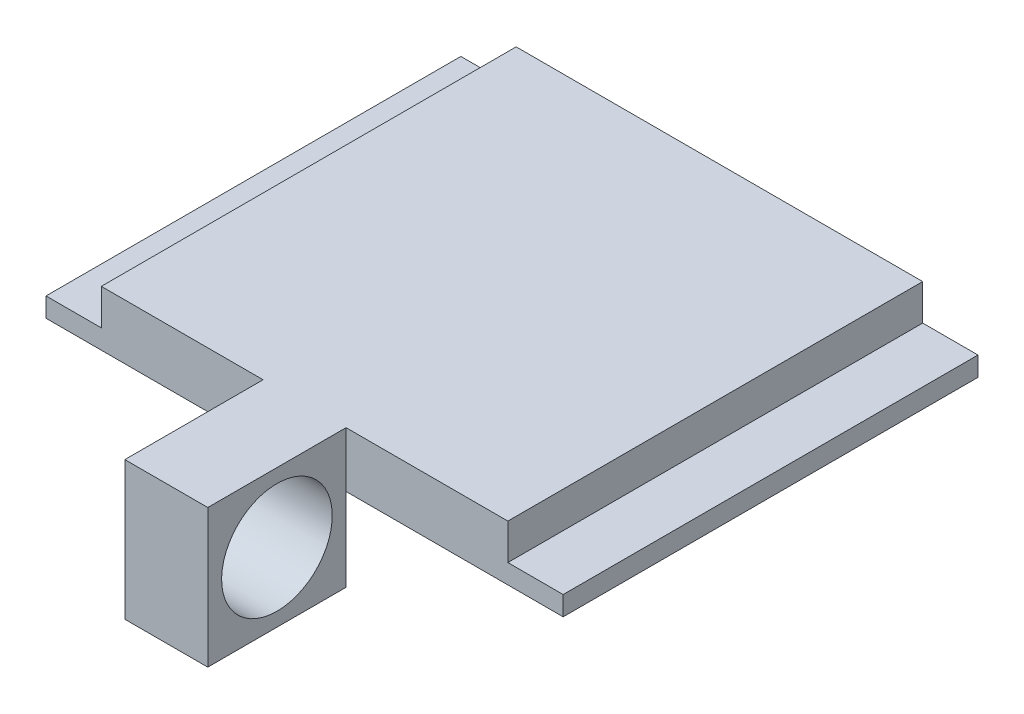
SolidWorks part; units mm, degrees
ref_plane "Front Plane" through (0, 0, 0) normal (0, 0, 1) x (1, 0, 0)
ref_plane "Top Plane" through (0, 0, 0) normal (0, 1, 0) x (1, 0, 0)
ref_plane "Right Plane" through (0, 0, 0) normal (1, 0, 0) x (0, 0, -1)
sketch "Sketch1" plane through (0, 0, 0) normal (0, 0, 1) x (1, 0, 0)
  line L16 (7.5, -0.65) -> (9.35, -0.65)
  line L17 (9.35, -0.65) -> (9.35, -1.35)
  line L18 (9.35, -1.35) -> (-9.35, -1.35)
  line L19 (-9.35, -1.35) -> (-9.35, -0.65)
  line L20 (-9.35, -0.65) -> (-7.5, -0.65)
  line L21 (7.35, 0.35) -> (7.35, -0.5)
  line L23 (-7.35, 0.35) -> (-7.35, -0.5)
  line L25 (-7.35, -0.5) -> (-7.35, -0.65)
  line L26 (-7.35, -0.65) -> (-7.5, -0.65)
  line L27 (7.5, -0.65) -> (7.35, -0.65)
  line L28 (7.35, -0.65) -> (7.35, -0.5)
  line L29 (-7.35, 0.35) -> (-7.35, 0.65)
  line L30 (-7.35, 0.65) -> (7.35, 0.65)
  line L31 (7.35, 0.65) -> (7.35, 0.35)
  point P0 (0, 0)
extrude "Boss-Extrude1" add sketch "Sketch1" against normal blind 15
sketch "Sketch2" plane through (0, 0, 0) normal (0, 0, 1) x (1, 0, 0)
  line L0 (0, 0.65) -> (0, -1.35)
  line L1 (7.35, 0.65) -> (-7.35, 0.65) construction
  line L2 (-9.35, -1.35) -> (9.35, -1.35) construction
  line L3 (-1.5, 0.65) -> (-1.5, -4.35)
  line L4 (-1.5, 2.15) -> (1.5, 2.15)
  line L5 (-1.5, 2.15) -> (-1.5, -2.85)
  line L6 (-1.5, -2.85) -> (1.5, -2.85)
  line L7 (1.5, 2.15) -> (1.5, -2.85)
  line L8 (-1.5, 2.15) -> (1.5, -2.85) construction
  line L9 (-1.5, -2.85) -> (1.5, 2.15) construction
  line L10 (-1.5, -4.35) -> (1.5, -4.35)
  line L11 (1.5, -4.35) -> (1.5, 0.65)
  line L12 (1.5, 0.65) -> (-1.5, 0.65)
  point P6 (0, -0.35)
  line M5 (7.35, 0.65) -> (-7.35, 0.65)
  line M9 (-9.35, -1.35) -> (9.35, -1.35)
  dimension "D1" = 5
  dimension "D2" = 3
extrude "Boss-Extrude3" add sketch "Sketch2" along normal blind 5 contours L10 L11 L6 L3 | L7 L3 L6 M9 | L3 L0 M5 M9 | L7 L0 M5 M9
sketch "Sketch4" plane through (-1.5, 0, 0) normal (-1, 0, 0) x (0, 0, 1)
  line L0 (0, -4.35) -> (5, -4.35)
  line L1 (2.5, -4.35) -> (2.5, -1.85)
  circle A0 centre (2.5, -1.85) radius 2
extrude "Cut-Extrude1" cut sketch "Sketch4" against normal blind 3
sketch "Sketch5" plane through (0, 0, 0) normal (0, 0, -1) x (-1, 0, 0)
  line L0 (-1.5, -1.35) -> (1.5, -1.35)
  line L1 (1.5, -1.35) -> (1.5, -4.35)
sketch "Sketch6" plane through (-1.5, 0, 0) normal (-1, 0, 0) x (0, 0, 1)
  line L0 (0, -1.35) -> (0, -4.35)
  line L1 (0, -1.35) -> (-3, -1.35)
  line L2 (-15, -1.35) -> (0, -1.35) construction
  line L3 (-3, -1.35) -> (0, -4.35)
